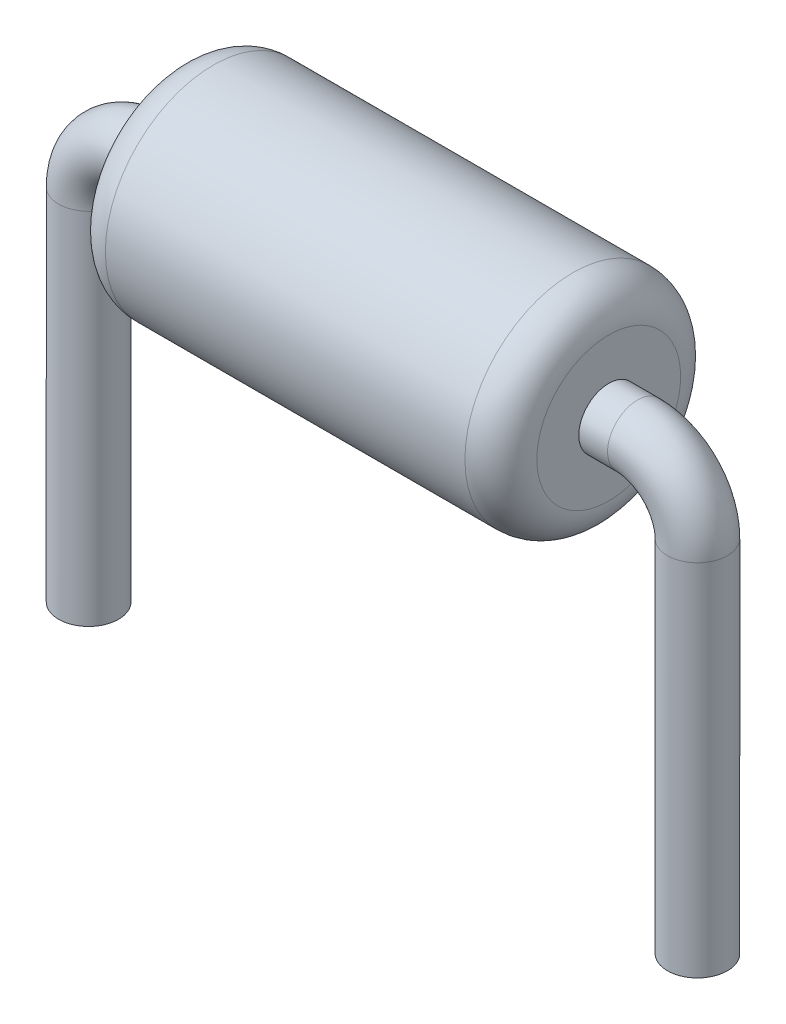
SolidWorks part; units mm, degrees
ref_plane "Front Plane" through (0, 0, 0) normal (0, 0, 1) x (1, 0, 0)
ref_plane "Top Plane" through (0, 0, 0) normal (0, 1, 0) x (1, 0, 0)
ref_plane "Right Plane" through (0, 0, 0) normal (1, 0, 0) x (0, 0, -1)
sketch "Sketch1" plane through (0, 0, 0) normal (0, 0, 1) x (1, 0, 0)
  line L1 (0, 0) -> (1.8, 0)
  line L2 (0, 0) -> (0, 0.9)
  line L3 (0, 0.9) -> (1.8, 0.9)
  line L4 (1.8, 0) -> (1.8, 0.9)
  dimension "D1" = 0.9
  dimension "D2" = 1.8
sketch "Sketch2" plane through (0, 0, 0) normal (0, 0, 1) x (1, 0, 0)
  line L0 (0, 0.9) -> (2.04, 0.9)
  line L1 (2.54, 0.4) -> (2.54, -2.6)
  line L2 (2.04, 0.4) -> (2.04, 0.9) construction
  line L3 (2.04, 0.4) -> (2.54, 0.4) construction
  arc A0 (2.04, 0.9) -> (2.54, 0.4) centre (2.04, 0.4) cw
  dimension "D1" = 0.5
  dimension "D2" = 2.54
  dimension "D3" = 3.5
revolve "Revolve1" add sketch "Sketch1" angle 360 about L3
sketch "Sketch3" plane through (1.8, 0, 0) normal (1, 0, 0) x (0, 0, -1)
  circle A0 centre (0, 0.9) radius 0.25
  dimension "D1" = 0.5
sweep "Sweep1" add profiles "Sketch3" path "Sketch2"
fillet "Fillet1" radius 0.3 1 edges at (1.8, 0.9, 0.9)
mirror "Mirror1" about plane through (0, 0, 0) normal (-1, 0, 0) of "Revolve1", "Sweep1", "Fillet1"
